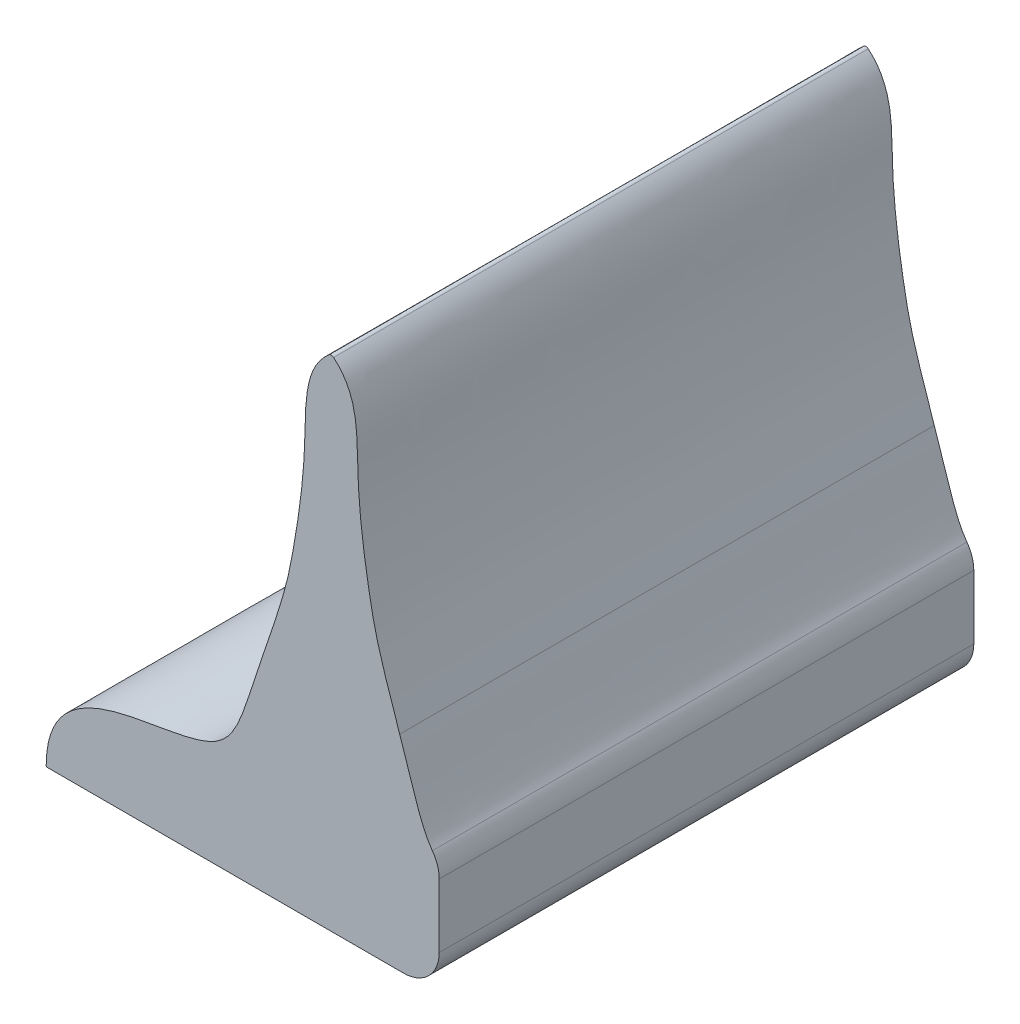
SolidWorks part; units mm, degrees
ref_plane "前视基准面" through (0, 0, 0) normal (0, 0, 1) x (1, 0, 0)
ref_plane "上视基准面" through (0, 0, 0) normal (0, 1, 0) x (1, 0, 0)
ref_plane "右视基准面" through (0, 0, 0) normal (1, 0, 0) x (0, 0, -1)
sketch "草图1" plane through (0, 0, 0) normal (0, 0, 1) x (1, 0, 0)
  line L0 (-16, 0) -> (16, 0)
  line L1 (0, 0) -> (0, 14.0324) construction
  spline S0 degree 3 poles (-3.8393, 11.5062) (-2.6615, 14.9201) (-2.2679, 16.5079) (-1.2442, 22.8904) (-1.6003, 26.8357) (0, 28.0648) knots 0 0 0 0 0.351321 0.67411 1 1 1 1
  spline S1 degree 3 poles (-3.8393, 11.5062) (-4.9391, 8.3183) (-5.6097, 3.7741) (-16.0153, 5.7253) (-16, 0) knots 0 0 0 0 0.346447 1 1 1 1
  spline S2 degree 3 poles (3.8393, 11.5062) (4.9391, 8.3183) (5.6097, 3.7741) (16.0153, 5.7253) (16, 0) knots 0 0 0 0 0.346447 1 1 1 1
  spline S3 degree 3 poles (3.8393, 11.5062) (2.6615, 14.9201) (2.2679, 16.5079) (1.2442, 22.8904) (1.6003, 26.8357) (0, 28.0648) knots 0 0 0 0 0.351321 0.67411 1 1 1 1
  dimension "D1" = 32
  dimension "D2" = 3
extrude "凸台-拉伸1" add sketch "草图1" along normal blind 30
sketch "草图2" plane through (0, 0, 30) normal (0, 0, 1) x (1, 0, 0)
  line L1 (6.0556, 14.5137) -> (56.4176, 14.5137)
  line L2 (6.0556, 14.5137) -> (6.0556, -6.0557)
  line L3 (6.0556, -6.0557) -> (56.4176, -6.0557)
  line L4 (56.4176, 14.5137) -> (56.4176, -6.0557)
  point P6 (53.5536, 6.5915)
  point P7 (5.7513, -18.6454)
  point P8 (0, 0)
extrude "切除-拉伸1" cut sketch "草图2" against normal blind 30
fillet "圆角1" radius 2 2 edges at (6.0556, 0, 15) (6.0556, 6.3233, 15)
fillet "圆角2" radius 0.2 1 edges at (0, 28.0648, 15)
fillet "圆角3" radius 0.05 1 edges at (-16, 0, 15)
